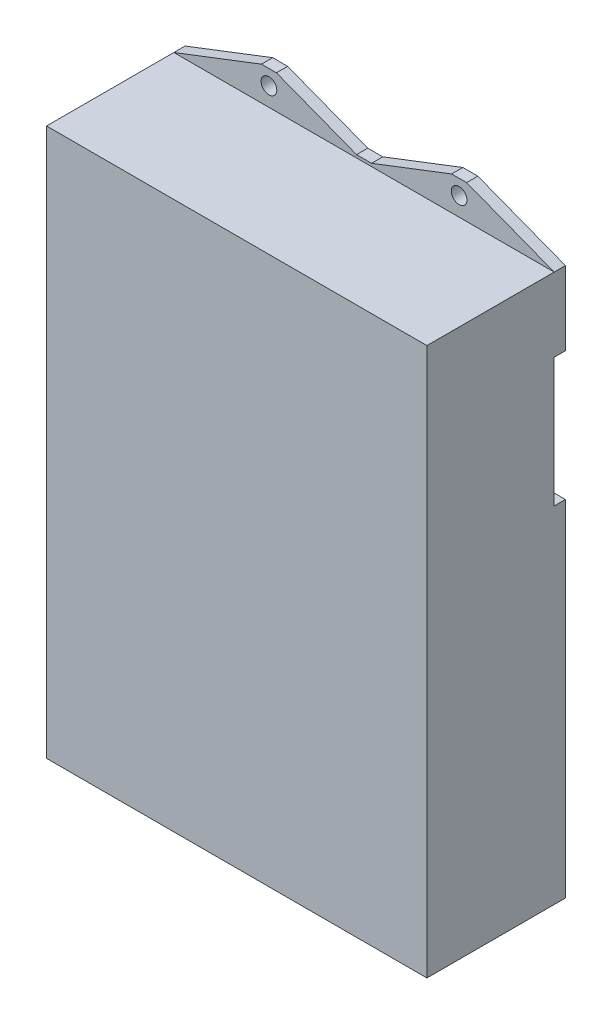
SolidWorks part; units mm, degrees
ref_plane "Plan de face" through (0, 0, 0) normal (0, 0, 1) x (1, 0, 0)
ref_plane "Plan de dessus" through (0, 0, 0) normal (0, 1, 0) x (1, 0, 0)
ref_plane "Plan de droite" through (0, 0, 0) normal (1, 0, 0) x (0, 0, -1)
sketch "Esquisse1" plane through (0, 0, 0) normal (0, 0, 1) x (1, 0, 0)
  line L0 (-50.8, -82.15) -> (-50.8, 82.15) construction
  line L1 (-50.8, 82.15) -> (50.8, 82.15) construction
  line L2 (50.8, 82.15) -> (50.8, -82.15) construction
  line L3 (50.8, -82.15) -> (-50.8, -82.15) construction
  line L4 (0, 0) -> (50.8, 0) construction
  line L5 (0, 0) -> (0, 82.15) construction
  line L6 (-50.8, 73.15) -> (-27.4, 82.15)
  line L7 (-27.4, 82.15) -> (-23.4, 82.15)
  line L8 (-23.4, 82.15) -> (-2, 73.9192)
  line L9 (-2, 73.9192) -> (2, 73.9192)
  line L10 (50.8, 73.15) -> (27.4, 82.15)
  line L11 (27.4, 82.15) -> (23.4, 82.15)
  line L12 (23.4, 82.15) -> (2, 73.9192)
  line L13 (50.8, -73.15) -> (27.4, -82.15)
  line L14 (27.4, -82.15) -> (23.4, -82.15)
  line L15 (23.4, -82.15) -> (2, -73.9192)
  line L16 (-2, -73.9192) -> (2, -73.9192)
  line L17 (-23.4, -82.15) -> (-2, -73.9192)
  line L18 (-27.4, -82.15) -> (-23.4, -82.15)
  line L19 (-50.8, -73.15) -> (-27.4, -82.15)
  line L20 (-25.4, 78.15) -> (-25.4, 87.1997) construction
  line L21 (-50.8, 73.15) -> (-50.8, 53.45)
  line L22 (-50.8, 53.45) -> (-43.2, 53.45)
  line L23 (-43.2, 53.45) -> (-43.2, 19.05)
  line L25 (-50.8, 19.05) -> (-50.8, -73.15)
  line L26 (50.8, 73.15) -> (50.8, 53.45)
  line L27 (50.8, 53.45) -> (43.2, 53.45)
  line L28 (43.2, 53.45) -> (43.2, 19.05)
  line L31 (-50.8, 19.05) -> (-43.2, 19.05)
  line L32 (43.2, 19.05) -> (50.8, 19.05)
  line L33 (50.8, 19.05) -> (50.8, -73.15)
  circle A0 centre (-25.4, -78.15) radius 2.1
  circle A1 centre (25.4, -78.15) radius 2.1
  circle A2 centre (-25.4, 78.15) radius 2.1
  circle A3 centre (25.4, 78.15) radius 2.1
  circle A4 centre (-48.1, -69.85) radius 1.5
  circle A5 centre (48.1, -69.85) radius 1.5
  circle A6 centre (-48.1, 69.85) radius 1.5
  circle A7 centre (48.1, 69.85) radius 1.5
  point P7 (0, 82.15)
  point P9 (50.8, 0)
  point P50 (44.1375, 19.05)
  point P51 (0, 0)
  dimension "D5" = 4.2
  dimension "D6" = 3
  dimension "D1" = 101.6
  dimension "D2" = 164.3
  dimension "D3" = 50.8
  dimension "D4" = 4
  dimension "D7" = 96.2
  dimension "D8" = 12.3
  dimension "D9" = 9
  dimension "D10" = 4
  dimension "D11" = 19.7
  dimension "D12" = 7.6
  dimension "D13" = 34.4
extrude "Boss.-Extru.1" add sketch "Esquisse1" along normal blind 3
sketch "Esquisse2" plane through (0, 0, 3) normal (0, 0, 1) x (1, 0, 0)
  line L1 (-50.8, 73.15) -> (50.8, 73.15)
  line L2 (-50.8, 73.15) -> (-50.8, -73.15)
  line L3 (-50.8, -73.15) -> (50.8, -73.15)
  line L4 (50.8, 73.15) -> (50.8, -73.15)
extrude "Boss.-Extru.2" add sketch "Esquisse2" along normal blind 34
